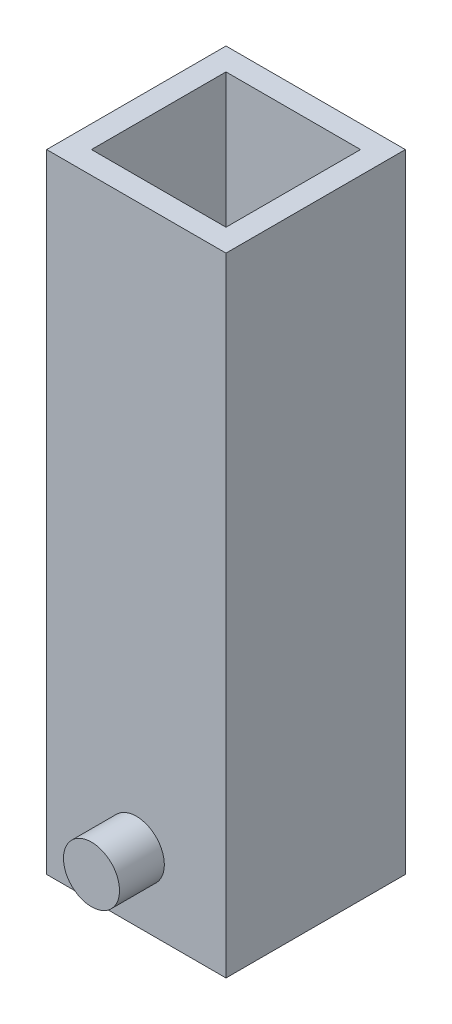
SolidWorks part; units mm, degrees
ref_plane "Front Plane" through (0, 0, 0) normal (0, 0, 1) x (1, 0, 0)
ref_plane "Top Plane" through (0, 0, 0) normal (0, 1, 0) x (1, 0, 0)
ref_plane "Right Plane" through (0, 0, 0) normal (1, 0, 0) x (0, 0, -1)
sketch "Sketch1" plane through (0, 0, 0) normal (0, 1, 0) x (1, 0, 0)
  line L1 (-40, 40) -> (40, 40)
  line L2 (-40, 40) -> (-40, -40)
  line L3 (-40, -40) -> (40, -40)
  line L4 (40, 40) -> (40, -40)
  line L5 (-40, 40) -> (40, -40) construction
  line L6 (-40, -40) -> (40, 40) construction
  line L7 (-30, 30) -> (30, 30)
  line L8 (-30, 30) -> (-30, -30)
  line L9 (-30, -30) -> (30, -30)
  line L10 (30, 30) -> (30, -30)
  line L11 (-30, 30) -> (30, -30) construction
  line L12 (-30, -30) -> (30, 30) construction
  point P0 (0, 0)
  point P6 (0, 0)
  dimension "D1" = 80
  dimension "D2" = 80
  dimension "D3" = 60
extrude "Boss-Extrude1" add sketch "Sketch1" along normal blind 250 and the other way blind 30
sketch "Sketch2" plane through (0, 0, 40) normal (0, 0, 1) x (1, 0, 0)
  circle A0 centre (0, 0) radius 12.5
extrude "Boss-Extrude2" add sketch "Sketch2" along normal blind 20
sketch "Sketch3" plane through (0, 0, -40) normal (0, 0, -1) x (-1, 0, 0)
  circle A0 centre (0, 0) radius 12.5
extrude "Boss-Extrude3" add sketch "Sketch3" along normal blind 25
sketch "Sketch8" plane through (0, 0, 0) normal (0, 0, 1) x (1, 0, 0)
  line L0 (0, 250) -> (0, -150) construction
  line L1 (-40, 250) -> (40, 250) construction
  line L2 (0, 250) -> (0, -150)
  dimension "D1" = 400
sketch "Sketch9" plane through (0, -30, 0) normal (0, -1, 0) x (1, 0, 0)
  circle A0 centre (0, 0) radius 5
